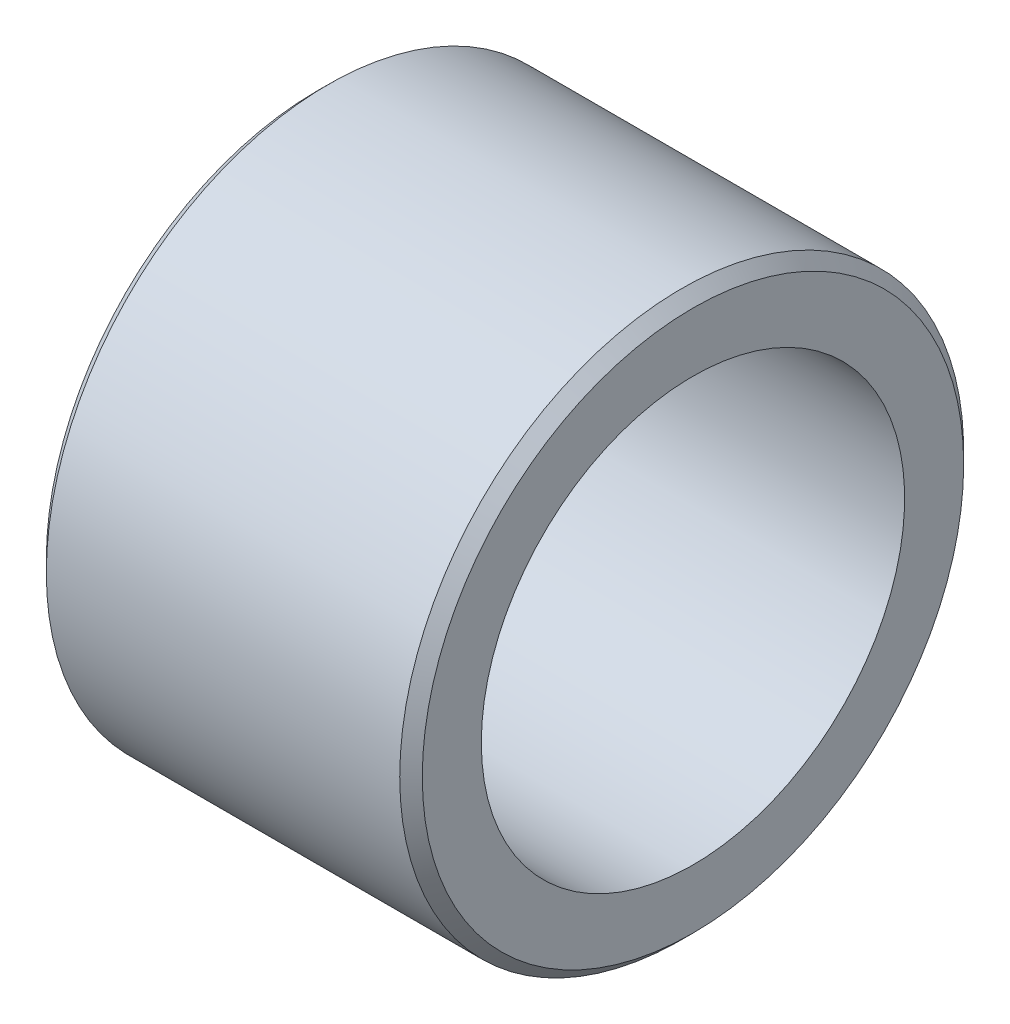
SolidWorks part; units mm, degrees
material "Brass"
ref_plane "Front Plane" through (0, 0, 0) normal (0, 0, 1) x (1, 0, 0)
ref_plane "Top Plane" through (0, 0, 0) normal (0, 1, 0) x (1, 0, 0)
ref_plane "Right Plane" through (0, 0, 0) normal (1, 0, 0) x (0, 0, -1)
sketch "Primary Sketch" plane through (0, 0, 0) normal (0, 0, 1) x (1, 0, 0)
  line L1 (0, 0) -> (12.7, 0) construction
  line L2 (0, 0) -> (0, 9.525) construction
  line L3 (0, 9.525) -> (12.7, 9.525) construction
  line L4 (12.7, 0) -> (12.7, 9.525) construction
  line L5 (0, 7.1501) -> (12.7, 7.1501)
  line L6 (0, 7.1501) -> (0, 9.525)
  line L7 (0, 9.525) -> (12.7, 9.525)
  line L8 (12.7, 7.1501) -> (12.7, 9.525)
  dimension "D1" = 12.7
  dimension "D2" = 14.3002
  dimension "D3" = 19.05
revolve "Primary Revolve" add sketch "Primary Sketch" angle 360 about L1
chamfer "Edge Chamfer" distance 0.381 angle 45 2 edges at (0, 0, 9.525) (12.7, 0, 9.525)
